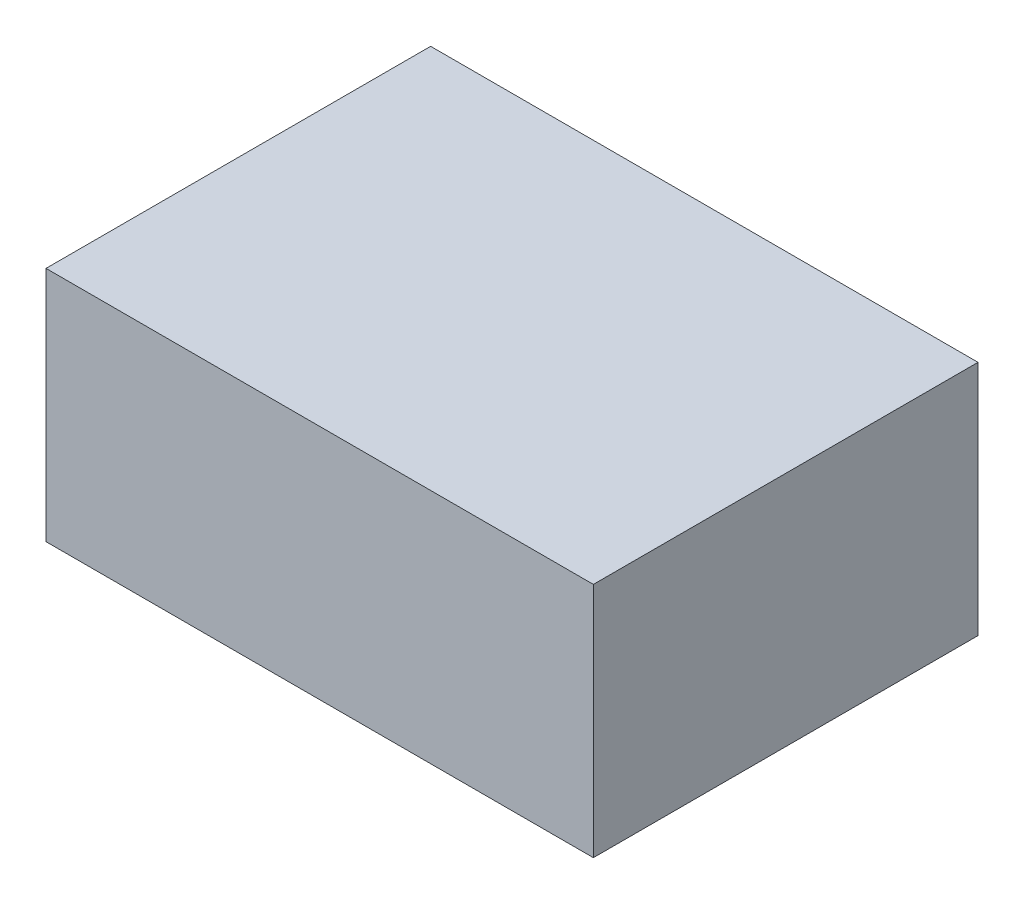
SolidWorks part; units mm, degrees
ref_plane "Front Plane" through (0, 0, 0) normal (0, 0, 1) x (1, 0, 0)
ref_plane "Top Plane" through (0, 0, 0) normal (0, 1, 0) x (1, 0, 0)
ref_plane "Right Plane" through (0, 0, 0) normal (1, 0, 0) x (0, 0, -1)
sketch "Sketch1" plane through (0, 0, 0) normal (0, 1, 0) x (1, 0, 0)
  line L1 (-46.99, -33.02) -> (46.99, -33.02)
  line L2 (-46.99, -33.02) -> (-46.99, 33.02)
  line L3 (-46.99, 33.02) -> (46.99, 33.02)
  line L4 (46.99, -33.02) -> (46.99, 33.02)
  line L5 (-46.99, -33.02) -> (46.99, 33.02) construction
  line L6 (-46.99, 33.02) -> (46.99, -33.02) construction
  point P0 (0, 0)
  dimension "D1" = 93.98
  dimension "D2" = 66.04
extrude "Boss-Extrude1" add sketch "Sketch1" along normal mid plane 40.64
